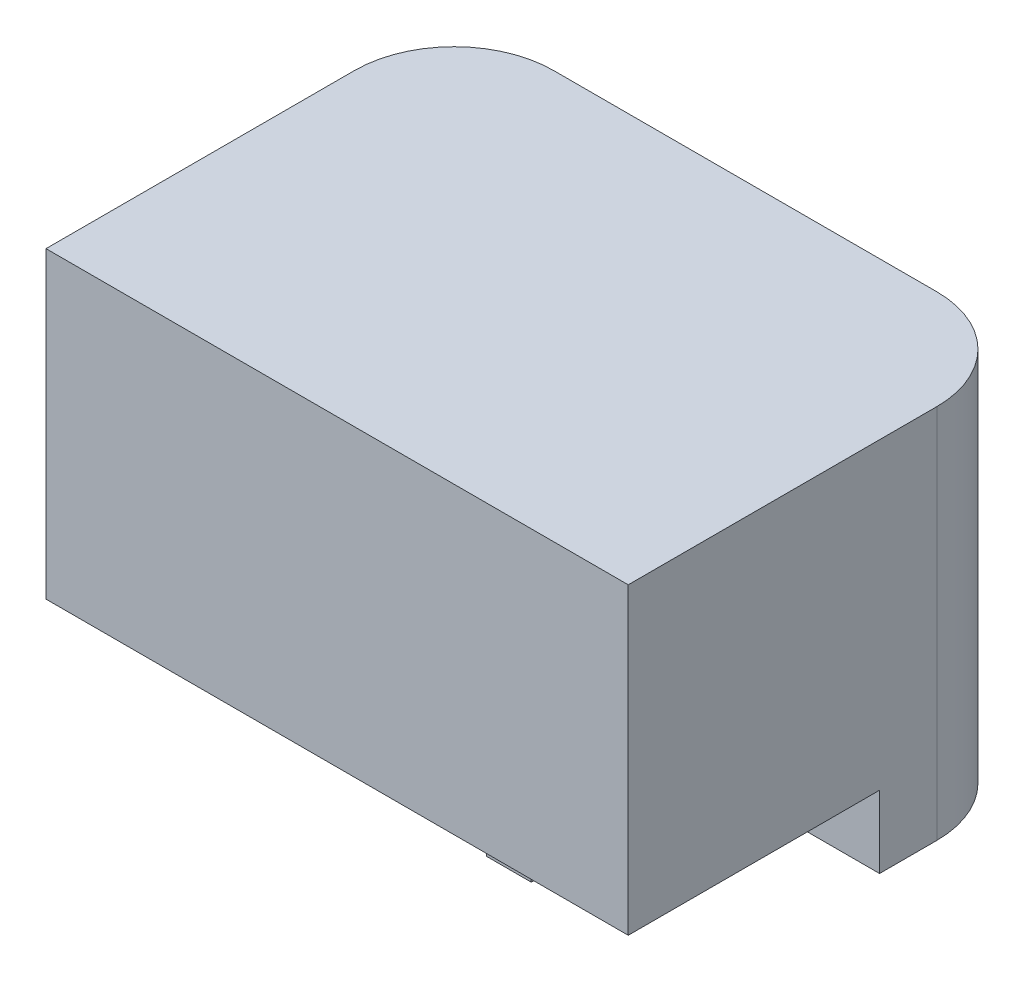
SolidWorks part; units mm, degrees
ref_plane "Front Plane" through (0, 0, 0) normal (0, 0, 1) x (1, 0, 0)
ref_plane "Top Plane" through (0, 0, 0) normal (0, 1, 0) x (1, 0, 0)
ref_plane "Right Plane" through (0, 0, 0) normal (1, 0, 0) x (0, 0, -1)
sketch "Sketch1" plane through (0, 0, 0) normal (0, 1, 0) x (1, 0, 0)
  line L1 (-117, 82) -> (117, 82)
  line L2 (-117, 82) -> (-117, -82)
  line L3 (-117, -82) -> (117, -82)
  line L4 (117, 82) -> (117, -82)
  line L5 (-117, 82) -> (117, -82) construction
  line L6 (-117, -82) -> (117, 82) construction
  point P0 (0, 0)
extrude "Boss-Extrude1" add sketch "Sketch1" along normal blind 151
sketch "Sketch2" plane through (-117, 0, 0) normal (-1, 0, 0) x (0, 0, 1)
  line L0 (82, 151) -> (82, 0) construction
  line L1 (115.5362, -17.0324) -> (-19, -17.0324)
  line L2 (115.5362, -17.0324) -> (115.5362, 29)
  line L3 (115.5362, 29) -> (-19, 29)
  line L4 (-19, -17.0324) -> (-19, 29)
  line L5 (-82, 0) -> (82, 0) construction
  dimension "D1" = 101
  dimension "D2" = 29
extrude "Cut-Extrude1" cut sketch "Sketch2" against normal through all
fillet "Fillet1" radius 40 2 edges at (117, 75.5, -82) (-117, 75.5, -82)
sketch "Sketch3" plane through (0, 29, 0) normal (0, -1, 0) x (1, 0, 0)
  line L0 (0, 82) -> (0, 26.6804) construction
  line L2 (-117, 82) -> (117, 82) construction
  line L3 (-9, 13) -> (9, 13)
  line L4 (-9, 13) -> (-9, -17)
  line L5 (-9, -17) -> (9, -17)
  line L6 (9, 13) -> (9, -17)
  line L7 (-9, 13) -> (9, -17) construction
  line L8 (-9, -17) -> (9, 13) construction
  point P1 (0, -2)
  dimension "D1" = 84
extrude "Boss-Extrude2" add sketch "Sketch3" along normal blind 70
sketch "Sketch4" plane through (-9, 0, 0) normal (-1, 0, 0) x (0, 0, 1)
  line L0 (82, 29) -> (-19, 29) construction
  circle A0 centre (0, -31) radius 3
  dimension "D1" = 60
extrude "Cut-Extrude2" cut sketch "Sketch4" against normal through all
